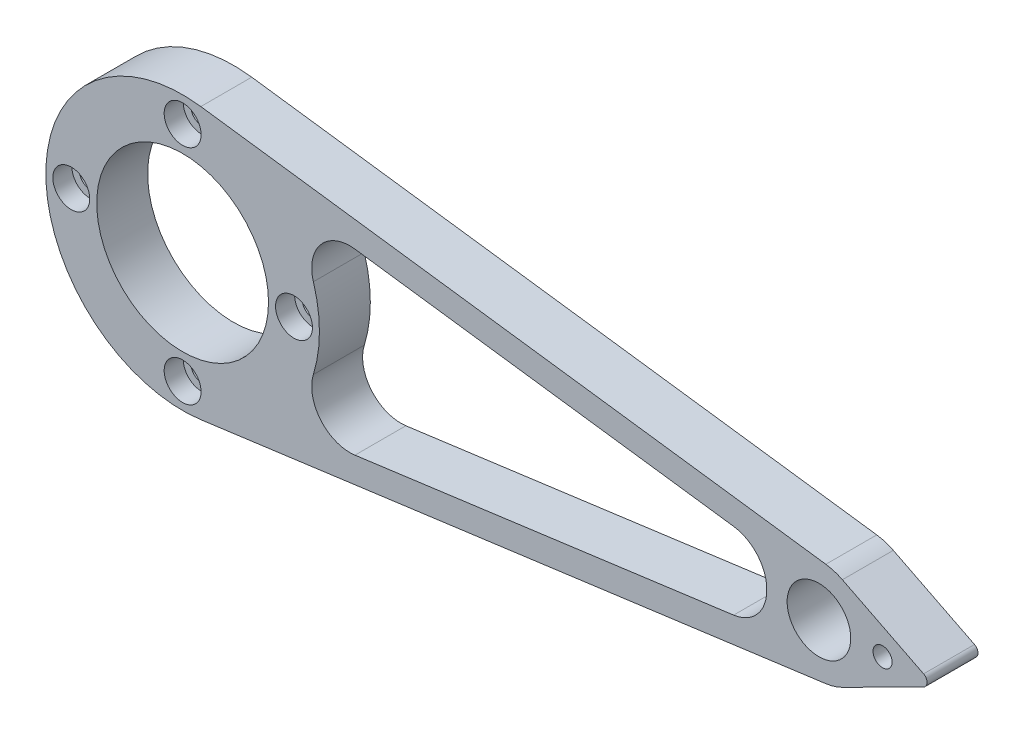
SolidWorks part; units mm, degrees
ref_plane "Plan de face" through (0, 0, 0) normal (0, 0, 1) x (1, 0, 0)
ref_plane "Plan de dessus" through (0, 0, 0) normal (0, 1, 0) x (1, 0, 0)
ref_plane "Plan de droite" through (0, 0, 0) normal (1, 0, 0) x (0, 0, -1)
sketch "Esquisse1" plane through (0, 0, 0) normal (0, 0, 1) x (1, 0, 0)
  circle A0 centre (0, 0) radius 17.5 construction
  circle A1 centre (0, 17.5) radius 1.7
  circle A2 centre (17.5, 0) radius 1.7
  circle A3 centre (0, -17.5) radius 1.7
  circle A4 centre (-17.5, 0) radius 1.7
  circle A5 centre (0, 0) radius 13.5
  circle A6 centre (0, 0) radius 21.5
  point P14 (0, 0)
  dimension "D1" = 35
  dimension "D2" = 3.4
  dimension "D4" = 4
  dimension "D5" = 4
  dimension "D3" = 4
extrude "Boss.-Extru.1" add sketch "Esquisse1" along normal blind 8
sketch "Esquisse2" plane through (0, 0, 8) normal (0, 0, 1) x (1, 0, 0)
  line L0 (0, 0) -> (100, 0) construction
  line L1 (2.8595, 21.309) -> (101.0906, 8.1272)
  line L2 (2.8595, -21.309) -> (101.0906, -8.1272)
  circle A0 centre (100, 0) radius 5
  arc A1 (101.0906, -8.1272) -> (101.0906, 8.1272) centre (100, 0) ccw
  circle A2 centre (0, 0) radius 21.5 construction
  arc A3 (2.8595, -21.309) -> (2.8595, 21.309) centre (0, 0) ccw
  dimension "D1" = 10
  dimension "D2" = 3.2
  dimension "D3" = 100
extrude "Boss.-Extru.2" add sketch "Esquisse2" against normal blind 8
sketch "Esquisse3" plane through (0, 0, 8) normal (0, 0, 1) x (1, 0, 0)
  line L0 (14.7065, 15.6834) -> (93.5784, 5.0994)
  line L1 (101.0906, 8.1272) -> (2.8595, 21.309) construction
  line L2 (0, 0) -> (100, 0) construction
  line L3 (14.7065, -15.6834) -> (93.5784, -5.0994)
  arc A0 (14.7065, -15.6834) -> (14.7065, 15.6834) centre (0, 0) ccw
  arc A1 (93.5784, 5.0994) -> (93.5784, -5.0994) centre (100, 0) ccw
  dimension "D1" = 4
extrude "Enlèv. mat.-Extru.1" cut sketch "Esquisse3" against normal through all
fillet "Congé1" radius 6 4 edges at (93.5784, -5.0994, 4) (93.5784, 5.0994, 4) (14.7065, -15.6834, 4) (14.7065, 15.6834, 4)
sketch "Esquisse4" plane through (0, 0, 8) normal (0, 0, 1) x (1, 0, 0)
  line L0 (100, 0) -> (116, 0) construction
  line L1 (103.69, 7.3228) -> (116.45, 0.893)
  line L2 (103.69, -7.3228) -> (116.45, -0.893)
  arc A0 (101.0906, -8.1272) -> (101.0906, 8.1272) centre (100, 0) ccw construction
  arc A1 (103.69, -7.3228) -> (103.69, 7.3228) centre (100, 0) ccw
  arc A2 (116.45, -0.893) -> (116.45, 0.893) centre (116, 0) ccw
  circle A3 centre (110, 0) radius 1.5
  dimension "D1" = 2
  dimension "D3" = 3
  dimension "D2" = 16
  dimension "D4" = 10
extrude "Boss.-Extru.3" add sketch "Esquisse4" against normal blind 8
sketch "Esquisse5" plane through (0, 0, 8) normal (0, 0, 1) x (1, 0, 0)
  circle A0 centre (0, 17.5) radius 2.9
  circle A1 centre (17.5, 0) radius 2.9
  circle A2 centre (0, -17.5) radius 2.9
  circle A3 centre (-17.5, 0) radius 2.9
  dimension "D1" = 5.8
extrude "Enlèv. mat.-Extru.2" cut sketch "Esquisse5" against normal blind 3
